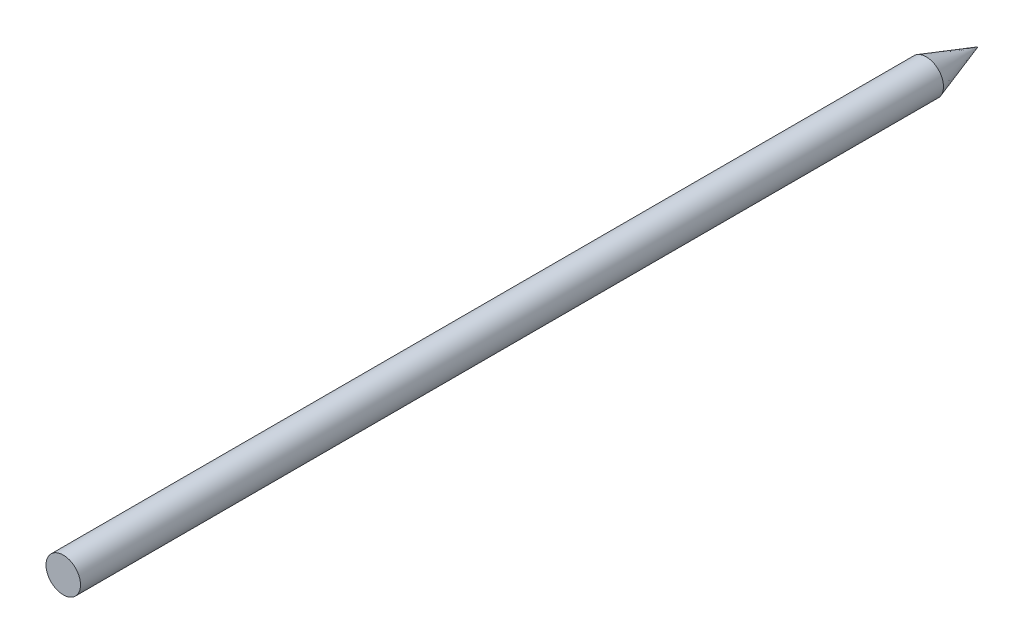
SolidWorks part; units mm, degrees
ref_plane "Front Plane" through (0, 0, 0) normal (0, 0, 1) x (1, 0, 0)
ref_plane "Top Plane" through (0, 0, 0) normal (0, 1, 0) x (1, 0, 0)
ref_plane "Right Plane" through (0, 0, 0) normal (1, 0, 0) x (0, 0, -1)
sketch "Sketch2" plane through (0, 0, 0) normal (0, 1, 0) x (1, 0, 0)
  line L0 (2.54, 0) -> (-2.54, 0)
  line L1 (-2.54, 0) -> (-2.54, 127)
  line L2 (-2.54, 127) -> (0, 134.62)
  line L3 (0, 134.62) -> (2.54, 127)
  line L4 (2.54, 127) -> (2.54, 0)
  line L5 (0, 134.62) -> (0, 0) construction
  point P3 (0, 134.62)
  point P7 (-2.54, 104.1788)
  dimension "D1" = 127
  dimension "D2" = 5.08
  dimension "D3" = 7.62
revolve "Revolve2" add sketch "Sketch2" angle 360 about L5
